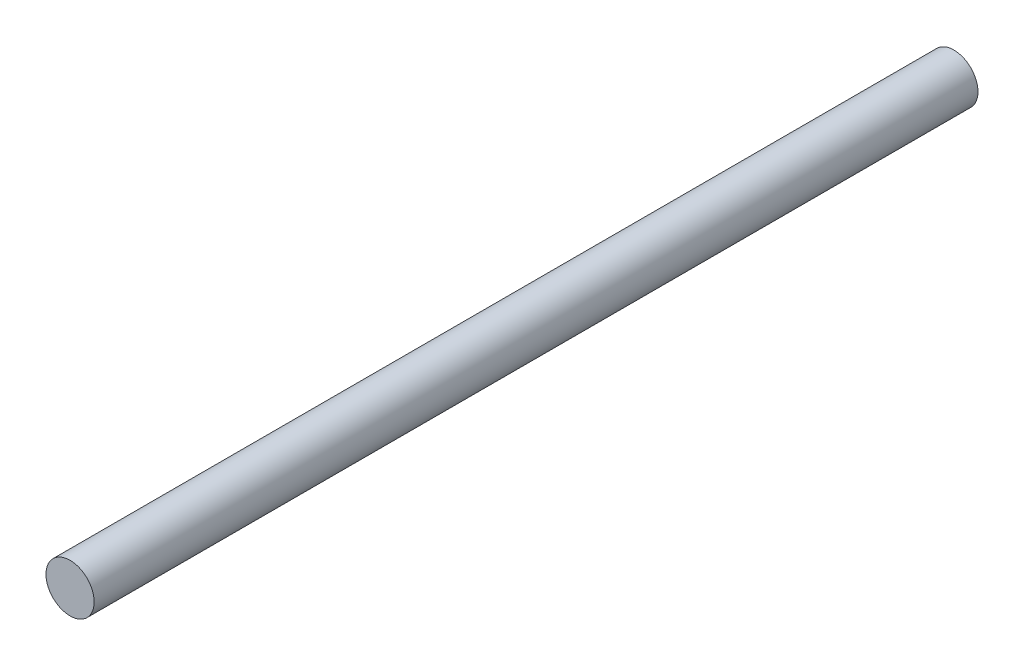
SolidWorks part; units mm, degrees
ref_plane "Front Plane" through (0, 0, 0) normal (0, 0, 1) x (1, 0, 0)
ref_plane "Top Plane" through (0, 0, 0) normal (0, 1, 0) x (1, 0, 0)
ref_plane "Right Plane" through (0, 0, 0) normal (1, 0, 0) x (0, 0, -1)
sketch "Sketch1" plane through (0, 0, 0) normal (0, 0, 1) x (1, 0, 0)
  circle A0 centre (0, 0) radius 3
  dimension "D1" = 6
extrude "Boss-Extrude1" add sketch "Sketch1" along normal blind 110
